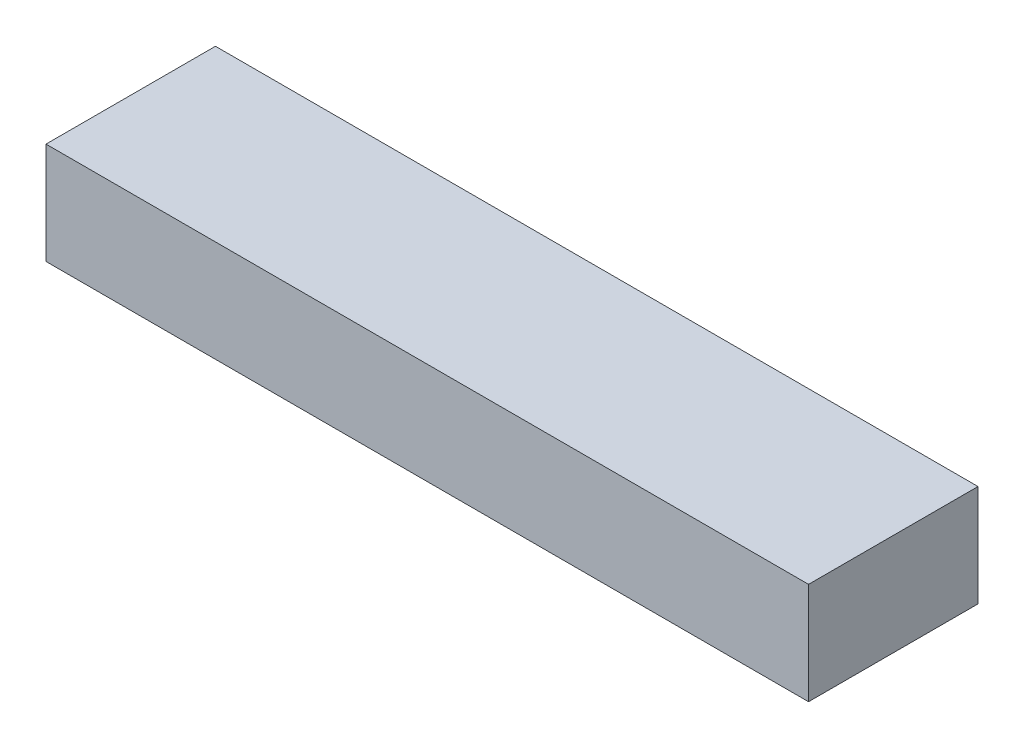
SolidWorks part; units mm, degrees
ref_plane "Płaszczyzna przednia" through (0, 0, 0) normal (0, 0, 1) x (1, 0, 0)
ref_plane "Płaszczyzna górna" through (0, 0, 0) normal (0, 1, 0) x (1, 0, 0)
ref_plane "Płaszczyzna prawa" through (0, 0, 0) normal (1, 0, 0) x (0, 0, -1)
sketch "Sketch1" plane through (0, 0, 0) normal (0, 1, 0) x (1, 0, 0)
  line L1 (-24.6567, -5.2039) -> (20.3433, -5.2039)
  line L2 (-24.6567, -5.2039) -> (-24.6567, 4.7961)
  line L3 (-24.6567, 4.7961) -> (20.3433, 4.7961)
  line L4 (20.3433, -5.2039) -> (20.3433, 4.7961)
  dimension "D1" = 45
  dimension "D2" = 10
extrude "Boss-Extrude1" add sketch "Sketch1" along normal blind 6
